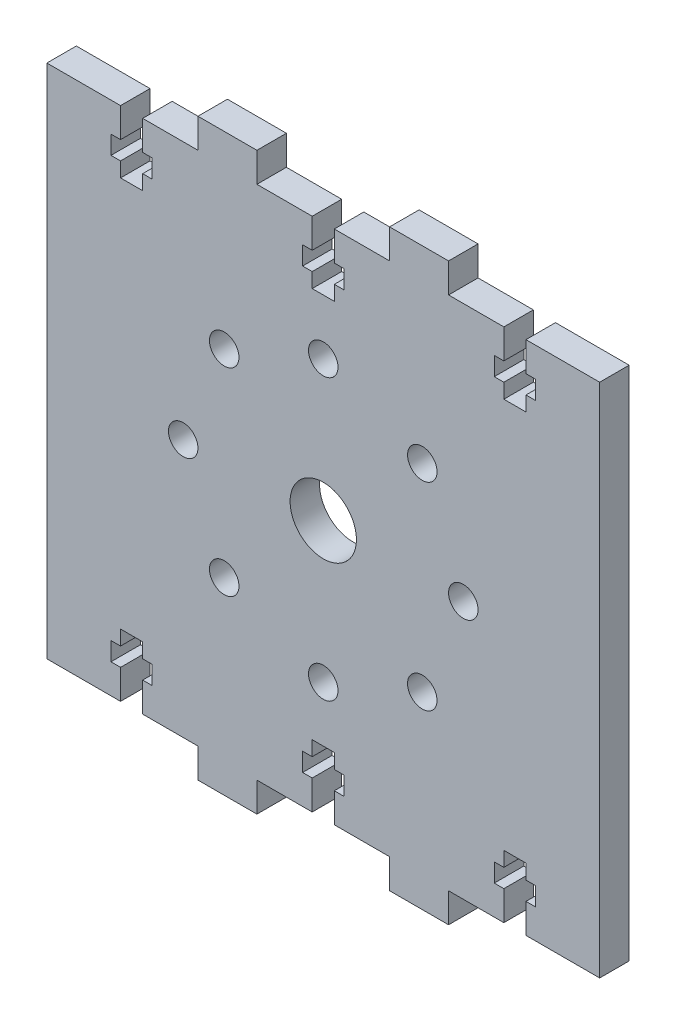
SolidWorks part; units mm, degrees
ref_plane "前视基准面" through (0, 0, 0) normal (0, 0, 1) x (1, 0, 0)
ref_plane "上视基准面" through (0, 0, 0) normal (0, 1, 0) x (1, 0, 0)
ref_plane "右视基准面" through (0, 0, 0) normal (1, 0, 0) x (0, 0, -1)
sketch "草图1" plane through (0, 0, 0) normal (0, 0, 1) x (1, 0, 0)
  line L0 (0, 0) -> (-25, 0) construction
  line L1 (-25, 25) -> (25, 25) construction
  line L2 (-25, 25) -> (-25, -25) construction
  line L3 (-25, -25) -> (25, -25) construction
  line L4 (25, 25) -> (25, -25) construction
  line L5 (0, 0) -> (0, 25) construction
  line L7 (-37.5, 35) -> (37.5, 35)
  line L8 (-37.5, 35) -> (-37.5, -35)
  line L9 (-37.5, -35) -> (37.5, -35)
  line L10 (37.5, 35) -> (37.5, -35)
  line L11 (-37.5, 35) -> (37.5, -35) construction
  line L12 (-37.5, -35) -> (37.5, 35) construction
  circle A0 centre (0, 0) radius 4.5
  circle A1 centre (19, 0) radius 2
  circle A3 centre (13.435, -13.435) radius 2
  circle A4 centre (0, -19) radius 2
  circle A5 centre (-13.435, -13.435) radius 2
  circle A6 centre (-19, 0) radius 2
  circle A7 centre (-13.435, 13.435) radius 2
  circle A8 centre (0, 19) radius 2
  circle A9 centre (13.435, 13.435) radius 2
  dimension "D1" = 9
  dimension "D2" = 4
  dimension "D4" = 8
  dimension "D3" = 19
  dimension "D5" = 25
  dimension "D6" = 50
  dimension "D7" = 70
  dimension "D8" = 75
extrude "凸台-拉伸1" add sketch "草图1" along normal blind 4
sketch "草图2" plane through (0, 0, 4) normal (0, 0, 1) x (1, 0, 0)
  line L0 (0, 35) -> (0, 36.3851) construction
  line L1 (37.5, 35) -> (-37.5, 35) construction
  line L2 (-1.5, 35) -> (1.5, 35)
  line L3 (1.5, 35) -> (1.5, 31)
  line L4 (1.5, 31) -> (2.8, 31)
  line L5 (2.8, 31) -> (2.8, 28.5)
  line L6 (2.8, 28.5) -> (1.5, 28.5)
  line L7 (1.5, 28.5) -> (1.5, 26.5)
  line L8 (1.5, 26.5) -> (-1.5, 26.5)
  line L9 (-1.5, 28.5) -> (-1.5, 26.5)
  line L10 (-2.8, 28.5) -> (-1.5, 28.5)
  line L11 (-2.8, 31) -> (-2.8, 28.5)
  line L12 (-1.5, 31) -> (-2.8, 31)
  line L13 (-1.5, 35) -> (-1.5, 31)
  line L14 (26, 35) -> (26, 40.1147) construction
  line L15 (13, 35) -> (13, 25.6052) construction
  line L16 (27.5, 35) -> (27.5, 31)
  line L17 (27.5, 31) -> (28.8, 31)
  line L18 (28.8, 31) -> (28.8, 28.5)
  line L19 (28.8, 28.5) -> (27.5, 28.5)
  line L20 (27.5, 28.5) -> (27.5, 26.5)
  line L21 (24.5, 26.5) -> (27.5, 26.5)
  line L22 (24.5, 28.5) -> (24.5, 26.5)
  line L23 (23.2, 28.5) -> (24.5, 28.5)
  line L24 (23.2, 31) -> (23.2, 28.5)
  line L25 (24.5, 31) -> (23.2, 31)
  line L26 (24.5, 35) -> (24.5, 31)
  line L27 (27.5, 35) -> (24.5, 35)
  line L28 (-27.5, 35) -> (-24.5, 35)
  line L29 (-24.5, 35) -> (-24.5, 31)
  line L30 (-24.5, 31) -> (-23.2, 31)
  line L31 (-23.2, 31) -> (-23.2, 28.5)
  line L32 (-23.2, 28.5) -> (-24.5, 28.5)
  line L33 (-24.5, 28.5) -> (-24.5, 26.5)
  line L34 (-24.5, 26.5) -> (-27.5, 26.5)
  line L35 (-27.5, 28.5) -> (-27.5, 26.5)
  line L36 (-28.8, 28.5) -> (-27.5, 28.5)
  line L37 (-28.8, 31) -> (-28.8, 28.5)
  line L38 (-27.5, 31) -> (-28.8, 31)
  line L39 (-27.5, 35) -> (-27.5, 31)
  line L40 (37.5, 0) -> (26, 0) construction
  line L41 (37.5, -35) -> (37.5, 35) construction
  line L42 (13, -35) -> (13, -25.6052) construction
  line L43 (26, -35) -> (26, -40.1147) construction
  line L44 (0, -35) -> (0, -36.3851) construction
  line L45 (-27.5, -35) -> (-27.5, -31)
  line L46 (-27.5, -31) -> (-28.8, -31)
  line L47 (-28.8, -31) -> (-28.8, -28.5)
  line L48 (-28.8, -28.5) -> (-27.5, -28.5)
  line L49 (-27.5, -28.5) -> (-27.5, -26.5)
  line L50 (-24.5, -26.5) -> (-27.5, -26.5)
  line L51 (-24.5, -28.5) -> (-24.5, -26.5)
  line L52 (-23.2, -28.5) -> (-24.5, -28.5)
  line L53 (-23.2, -31) -> (-23.2, -28.5)
  line L54 (-24.5, -31) -> (-23.2, -31)
  line L55 (-24.5, -35) -> (-24.5, -31)
  line L56 (-27.5, -35) -> (-24.5, -35)
  line L57 (27.5, -35) -> (24.5, -35)
  line L58 (24.5, -35) -> (24.5, -31)
  line L59 (24.5, -31) -> (23.2, -31)
  line L60 (23.2, -31) -> (23.2, -28.5)
  line L61 (23.2, -28.5) -> (24.5, -28.5)
  line L62 (24.5, -28.5) -> (24.5, -26.5)
  line L63 (24.5, -26.5) -> (27.5, -26.5)
  line L64 (27.5, -28.5) -> (27.5, -26.5)
  line L65 (28.8, -28.5) -> (27.5, -28.5)
  line L66 (28.8, -31) -> (28.8, -28.5)
  line L67 (27.5, -31) -> (28.8, -31)
  line L68 (27.5, -35) -> (27.5, -31)
  line L69 (-1.5, -35) -> (-1.5, -31)
  line L70 (-1.5, -31) -> (-2.8, -31)
  line L71 (-2.8, -31) -> (-2.8, -28.5)
  line L72 (-2.8, -28.5) -> (-1.5, -28.5)
  line L73 (-1.5, -28.5) -> (-1.5, -26.5)
  line L74 (1.5, -26.5) -> (-1.5, -26.5)
  line L75 (1.5, -28.5) -> (1.5, -26.5)
  line L76 (2.8, -28.5) -> (1.5, -28.5)
  line L77 (2.8, -31) -> (2.8, -28.5)
  line L78 (1.5, -31) -> (2.8, -31)
  line L79 (1.5, -35) -> (1.5, -31)
  line L80 (-1.5, -35) -> (1.5, -35)
  point P13 (0, 26.5)
  point P34 (26, 26.5)
  point P47 (-26, 26.5)
  point P94 (-26, -26.5)
  point P95 (26, -26.5)
  point P96 (0, -26.5)
  dimension "D1" = 1.5
  dimension "D2" = 2.5
  dimension "D3" = 4
  dimension "D4" = 2
  dimension "D5" = 2.8
  dimension "D6" = 26
  dimension "D7" = 13
extrude "切除-拉伸1" cut sketch "草图2" against normal blind 4
sketch "草图3" plane through (0, 0, 4) normal (0, 0, 1) x (1, 0, 0)
  line L0 (-13, -35) -> (-13, -39) construction
  line L1 (-24.5, -35) -> (-1.5, -35) construction
  line L2 (-17, -39) -> (-9, -39)
  line L3 (-9, -39) -> (-9, -35)
  line L4 (-9, -35) -> (-17, -35)
  line L5 (-9, -39) -> (-17, -39)
  line L6 (-17, -39) -> (-17, -35)
  line L7 (-17, -35) -> (-9, -35)
  line L8 (0, -32.5) -> (0, -33.42) construction
  line L9 (-9, -39) -> (-9, -35)
  line L10 (-17, -39) -> (-17, -35)
  line L11 (13, -35) -> (13, -39) construction
  line L12 (17, -39) -> (17, -35)
  line L13 (9, -39) -> (9, -35)
  line L14 (17, -35) -> (9, -35)
  line L15 (17, -39) -> (17, -35)
  line L16 (9, -39) -> (17, -39)
  line L17 (9, -35) -> (17, -35)
  line L18 (9, -39) -> (9, -35)
  line L19 (17, -39) -> (9, -39)
  line L20 (37.5, 0) -> (27.3537, 0) construction
  line L21 (37.5, -35) -> (37.5, 35) construction
  line L22 (13, 35) -> (13, 39) construction
  line L23 (0, 32.5) -> (0, 33.42) construction
  line L24 (-13, 35) -> (-13, 39) construction
  line L25 (17, 39) -> (9, 39)
  line L26 (9, 39) -> (9, 35)
  line L27 (9, 35) -> (17, 35)
  line L28 (9, 39) -> (17, 39)
  line L29 (17, 39) -> (17, 35)
  line L30 (17, 35) -> (9, 35)
  line L31 (9, 39) -> (9, 35)
  line L32 (17, 39) -> (17, 35)
  line L33 (-17, 39) -> (-17, 35)
  line L34 (-9, 39) -> (-9, 35)
  line L35 (-17, 35) -> (-9, 35)
  line L36 (-17, 39) -> (-17, 35)
  line L37 (-9, 39) -> (-17, 39)
  line L38 (-9, 35) -> (-17, 35)
  line L39 (-9, 39) -> (-9, 35)
  line L40 (-17, 39) -> (-9, 39)
extrude "凸台-拉伸2" add sketch "草图3" against normal blind 4 contours L6 L2 L3 L4 | L13 L16 L12 L14 | L29 L25 L26 L27 | L34 L37 L33 L35
sketch "草图4" plane through (0, -35, 0) normal (0, -1, 0) x (1, 0, 0)
  line L0 (-1.5, 2) -> (1.5, 2)
  line L1 (-1.5, 0) -> (-1.5, 4) construction
  line L2 (1.5, 0) -> (1.5, 4) construction
  circle A0 centre (0, 2) radius 1.5
sketch "草图5" plane through (0, 35, 0) normal (0, 1, 0) x (1, 0, 0)
  line L0 (1.5, -2) -> (-1.5, -2)
  line L1 (1.5, 0) -> (1.5, -4) construction
  line L2 (-1.5, 0) -> (-1.5, -4) construction
  circle A0 centre (0, -2) radius 1.5
